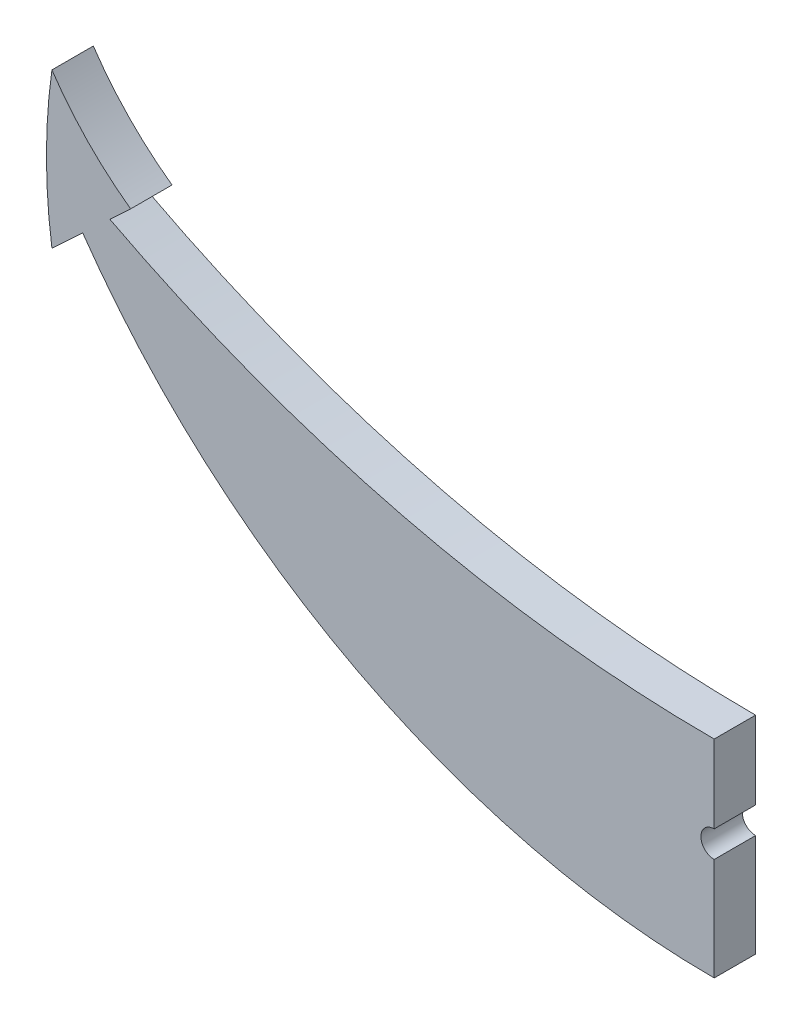
SolidWorks part; units mm, degrees
ref_plane "Спереди" through (0, 0, 0) normal (0, 0, 1) x (1, 0, 0)
ref_plane "Сверху" through (0, 0, 0) normal (0, 1, 0) x (1, 0, 0)
ref_plane "Справа" through (0, 0, 0) normal (1, 0, 0) x (0, 0, -1)
sketch "Эскиз1" plane through (0, 0, 0) normal (0, 0, 1) x (1, 0, 0)
  line L0 (-54.2129, -317.7119) -> (117.7871, -317.7119) construction
  line L1 (-80, 11.3475) -> (-76.2874, 14.8095)
  line L2 (0, 0) -> (0, -9.4)
  line L3 (0, 0) -> (15.8959, 0) construction
  line L4 (0, -25) -> (16.2355, -25) construction
  line L5 (-73, 17.8751) -> (-70.4924, 20.2134)
  line L6 (-76.2874, 14.8095) -> (-73, 17.8751) construction
  line L7 (0, -12.6) -> (0, -25)
  arc A0 (0, 0) -> (-73, 17.8751) centre (0, 158) cw
  arc A1 (0, -25) -> (-76.2874, 14.8095) centre (0, 68) cw
  arc A2 (-80, 30) -> (-80, 11.3475) centre (-14.6623, 20.6737) ccw
  arc A3 (-80, 30) -> (-70.4924, 20.2134) centre (-47.7045, 51.8633) ccw
  arc A4 (0, -9.4) -> (0, -12.6) centre (0, -11) ccw
  point P18 (0, 0)
  dimension "D3" = 158
  dimension "D4" = 93
  dimension "D9" = 39
  dimension "D10" = 66
  dimension "D13" = 3.2
  dimension "D1" = 172
  dimension "D2" = 25
  dimension "D5" = 73
  dimension "D6" = 47
  dimension "D7" = 80
  dimension "D8" = 30
  dimension "D11" = 13
  dimension "D12" = 80
  dimension "D14" = 14
extrude "Бобышка-Вытянуть1" add sketch "Эскиз1" along normal blind 5
